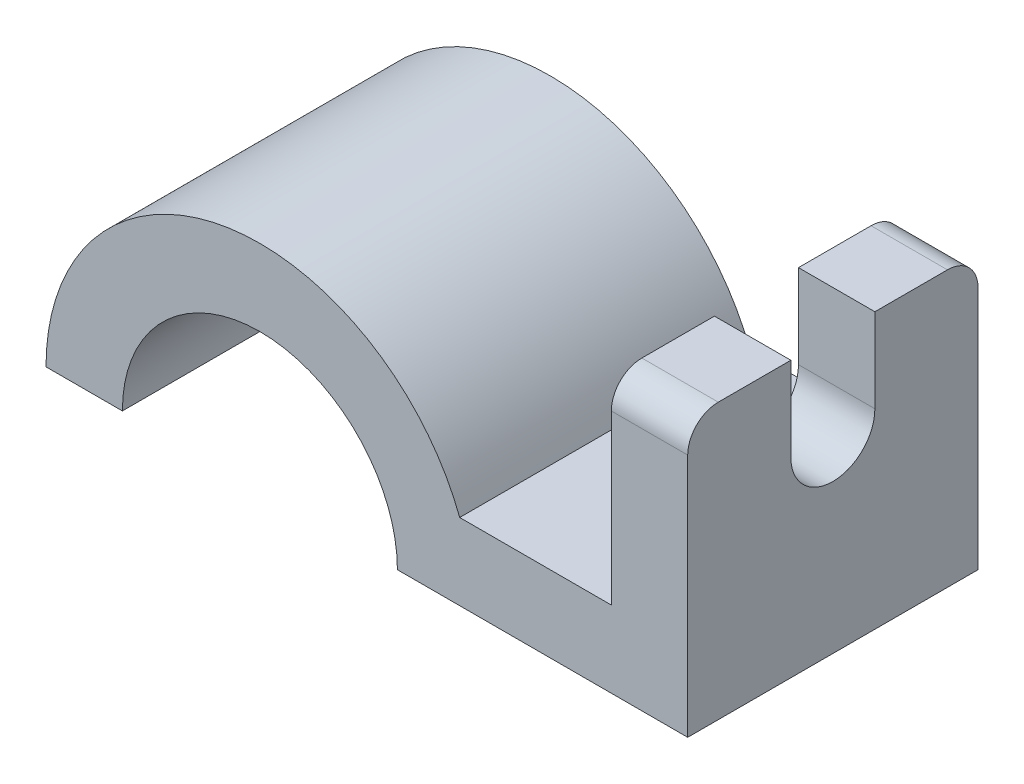
SolidWorks part; units mm, degrees
ref_plane "前基準面" through (0, 0, 0) normal (0, 0, 1) x (1, 0, 0)
ref_plane "上基準面" through (0, 0, 0) normal (0, 1, 0) x (1, 0, 0)
ref_plane "右基準面" through (0, 0, 0) normal (1, 0, 0) x (0, 0, -1)
sketch "草圖1" plane through (0, 0, 0) normal (1, 0, 0) x (0, 0, -1)
  line L0 (0, 0) -> (38, 0)
  line L1 (38, 0) -> (38, 36)
  line L2 (38, 36) -> (24.5, 36)
  line L3 (24.5, 36) -> (24.5, 25)
  line L4 (13.5, 25) -> (13.5, 36)
  line L5 (13.5, 36) -> (0, 36)
  line L6 (0, 36) -> (0, 0)
  line L7 (19, 25) -> (19, 38.0113) construction
  arc A0 (24.5, 25) -> (13.5, 25) centre (19, 25) cw
  dimension "D1" = 11
  dimension "D2" = 25
  dimension "D3" = 38
  dimension "D4" = 36
extrude "填料-伸長1" add sketch "草圖1" along normal blind 10
fillet "圓角1" radius 4 2 edges at (5, 36, -38) (5, 36, 0)
sketch "草圖2" plane through (0, 0, 0) normal (0, 0, 1) x (1, 0, 0)
  line L0 (-64, 0) -> (-74, 0)
  line L1 (0, 10) -> (0, 0)
  line L2 (0, 0) -> (-28, 0)
  line L4 (-64, 0) -> (-74.4009, 0) construction
  line L5 (0, 10) -> (-19.8466, 10)
  line L8 (-74.4009, 0) -> (-74.4009, 7.3218) construction
  line L10 (-69.1108, 15.808) -> (-69.1108, 15.808) construction
  line L11 (-69.1108, 15.808) -> (-69.1108, 15.808) construction
  arc A0 (-19.8466, 10) -> (-74, 0) centre (-46, 0) ccw
  arc A1 (-28, 0) -> (-64, 0) centre (-46, 0) ccw
  arc A2 (-18, 0) -> (-74, 0) centre (-46, 0) ccw construction
  arc A4 (-19.8466, 10) -> (-69.1108, 15.808) centre (-46, 0) ccw construction
  dimension "D1" = 18
  dimension "D2" = 10
  dimension "D3" = 56
extrude "填料-伸長2" add sketch "草圖2" against normal blind 38
